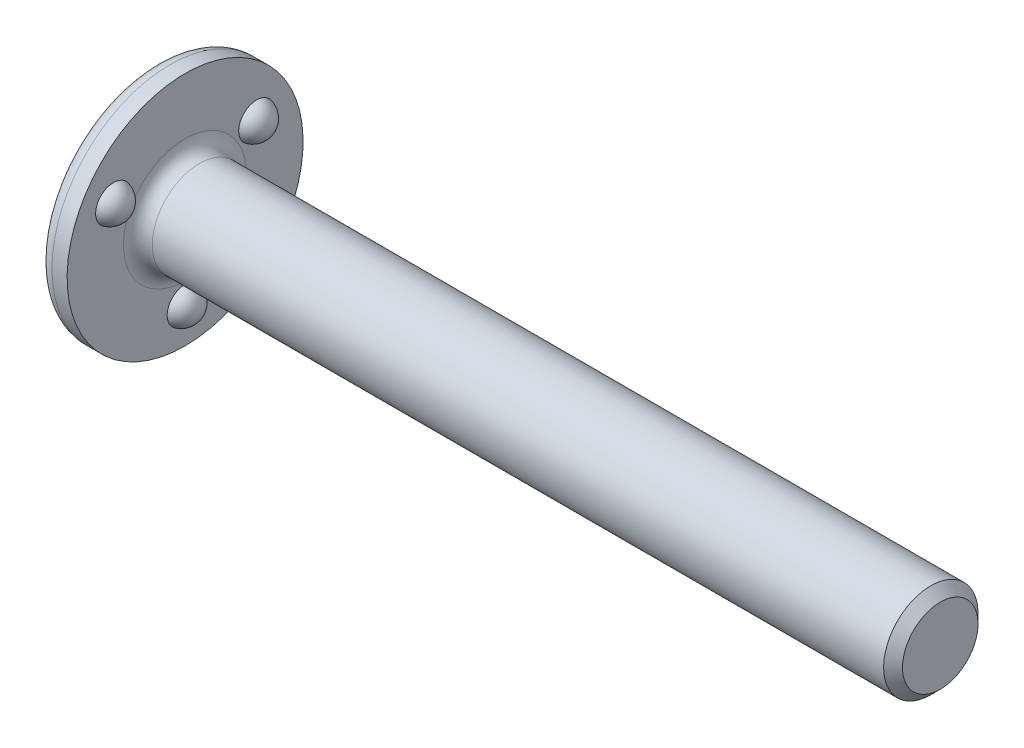
SolidWorks part; units mm, degrees
ref_plane "Front" through (0, 0, 0) normal (0, 0, 1) x (1, 0, 0)
ref_plane "Top" through (0, 0, 0) normal (0, 1, 0) x (1, 0, 0)
ref_plane "Right" through (0, 0, 0) normal (1, 0, 0) x (0, 0, -1)
sketch "Sketch1" plane through (0, 0, 0) normal (0, 0, 1) x (1, 0, 0)
  line L0 (0, 0) -> (0, 7.9375)
  line L1 (0, 7.9375) -> (1.9844, 7.9375)
  line L2 (1.9844, 7.9375) -> (1.9844, 3.175)
  line L3 (1.9844, 3.175) -> (52.7844, 3.175)
  line L4 (52.7844, 3.175) -> (52.7844, 0)
  line L5 (0, 0) -> (52.7844, 0) construction
  line L6 (0, 0) -> (52.7844, 0)
  dimension "Base Diameter" = 15.875
  dimension "Shaft Diameter" = 6.35
  dimension "Base Thickness" = 1.9844
  dimension "Shaft Length" = 50.8
revolve "Revolve1" add sketch "Sketch1" angle 360 about L5
chamfer "Chamfer1" distance 0.635 angle 45 1 edges at (52.7844, -3.175, 0)
sketch "Sketch4" plane through (0, 0, 0) normal (0, 0, 1) x (1, 0, 0)
  line L0 (1.9844, -3.175) -> (1.9844, -7.9375) construction
  line L1 (1.9844, -3.175) -> (1.9844, 3.175) construction
  line L2 (1.9844, -7.9375) -> (1.9844, 7.9375) construction
  line L3 (1.9844, -5.5563) -> (0, -5.5563) construction
  line L4 (0, 7.9375) -> (0, -7.9375) construction
  line L5 (1.9844, -5.5563) -> (1.9844, -4.3498)
  line L6 (1.9844, -5.5563) -> (2.9496, -5.5563)
  line L7 (0.9922, -5.5563) -> (0.9922, 7.9375) construction
  line L8 (1.9844, 7.9375) -> (0, 7.9375) construction
  line L9 (2.9496, -5.5563) -> (2.9496, -4.3498) construction
  line L10 (0, -5.5563) -> (-0.9652, -5.5563)
  line L11 (0, -5.5563) -> (0, -4.3498)
  arc A0 (2.9496, -5.5563) -> (1.9844, -4.3498) centre (1.7129, -5.5563) ccw
  arc A1 (-0.9652, -5.5563) -> (0, -4.3498) centre (0.2715, -5.5563) cw
  dimension "P" = 2.413
  dimension "F" = 0.9652
sketch "Sketch3" [suppressed] plane through (0, 0, 0) normal (0, 0, 1) x (1, 0, 0)
  line L0 (1.1906, 3.175) -> (1.1906, 1.5875) construction
  line L2 (1.1906, -1.5875) -> (1.1906, 1.5875) construction
  line L5 (1.1906, 2.3812) -> (0, 2.3812) construction
  line L6 (0, 3.175) -> (0, -3.175) construction
  line L7 (0, 2.3812) -> (-0.4572, 2.3812)
  line L8 (0, 2.3812) -> (0, 2.9527)
  line L9 (-0.4572, 2.3812) -> (-0.4572, 2.9527) construction
  arc A0 (-0.4572, 2.3812) -> (0, 2.9527) centre (0.1286, 2.3812) cw
  arc A1 (0, 2.9527) -> (-0.4572, 2.3812) centre (0.1286, 2.3812) ccw construction
revolve "Revolve3" [suppressed] add sketch "Sketch3" angle 360 about L5
pattern_circular "CirPattern2" [suppressed] count 3 over 360
fillet "Fillet2" [suppressed] radius 0.9652
sketch "Sketch2" plane through (0, 0, 0) normal (0, 0, 1) x (1, 0, 0)
  line L0 (1.9844, -7.9375) -> (1.9844, -3.175) construction
  line L1 (1.9844, -3.175) -> (1.9844, 3.175) construction
  line L2 (1.9844, -7.9375) -> (1.9844, 7.9375) construction
  line L3 (1.9844, -5.5563) -> (2.9496, -5.5563)
  line L4 (1.9844, -5.5563) -> (1.9844, -4.3498)
  line L5 (1.9844, -5.5563) -> (0, -5.5563) construction
  line L6 (0, 7.9375) -> (0, -7.9375) construction
  line L7 (2.9496, -5.5563) -> (2.9496, -4.3498) construction
  arc A0 (2.9496, -5.5563) -> (1.9844, -4.3498) centre (1.7129, -5.5563) ccw
  point P8 (1.9844, -5.5563)
revolve "Revolve2" add sketch "Sketch2" angle 360 about L5
pattern_circular "CirPattern1" count 3 over 360 about axis through (0, 0, 0) along (1, 0, 0) of "Revolve2"
fillet "Fillet1" radius 0.9652 2 edges at (0, -7.9375, 0) (1.9844, -3.175, 0)
equation "\"D1@Chamfer1\" = \"Shaft Diameter@Sketch1\"*.1"
equation "\"D1@Fillet1\" = \"F@Sketch4\""
equation "\"D1@Fillet2\" = \"F@Sketch4\""
